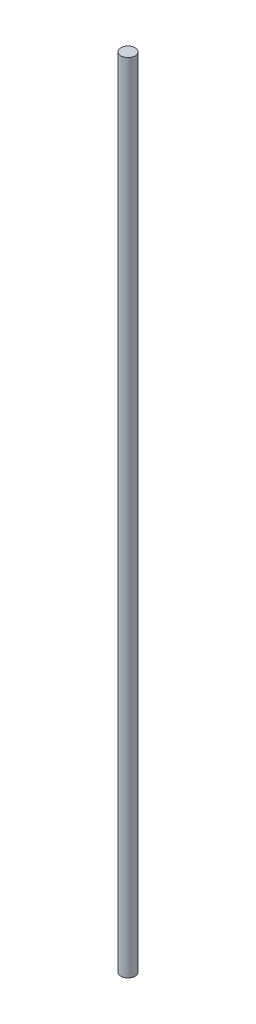
SolidWorks part; units mm, degrees
ref_plane "Front Plane" through (0, 0, 0) normal (0, 0, 1) x (1, 0, 0)
ref_plane "Top Plane" through (0, 0, 0) normal (0, 1, 0) x (1, 0, 0)
ref_plane "Right Plane" through (0, 0, 0) normal (1, 0, 0) x (0, 0, -1)
sketch "Sketch1" plane through (0, 0, 0) normal (0, 1, 0) x (1, 0, 0)
  circle A0 centre (-20.4401, 20.576) radius 2
extrude "Boss-Extrude1" add sketch "Sketch1" along normal blind 225
